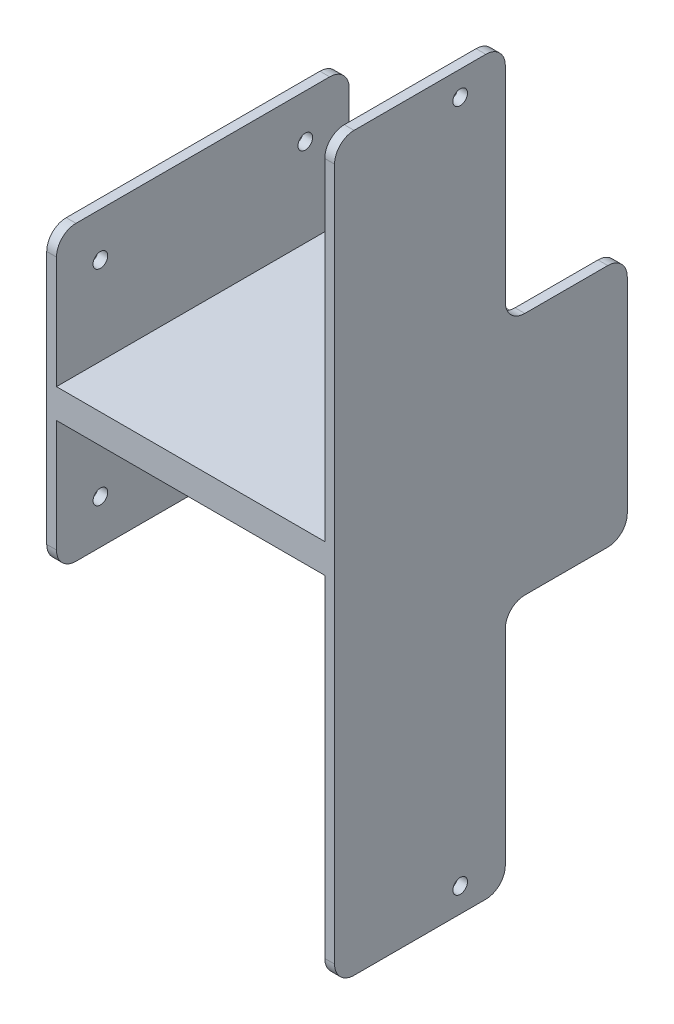
SolidWorks part; units mm, degrees
ref_plane "前视基准面" through (0, 0, 0) normal (0, 0, 1) x (1, 0, 0)
ref_plane "上视基准面" through (0, 0, 0) normal (0, 1, 0) x (1, 0, 0)
ref_plane "右视基准面" through (0, 0, 0) normal (1, 0, 0) x (0, 0, -1)
sketch "草图1" plane through (0, 0, 0) normal (0, 0, 1) x (1, 0, 0)
  line L0 (0, 0) -> (0, 50000) construction
  line L5 (-29.5, 30) -> (-27.5, 30)
  line L6 (-29.5, 30) -> (-29.5, -30)
  line L7 (-29.5, -30) -> (-27.5, -30)
  line L8 (-27.5, 30) -> (-27.5, 3)
  line L9 (27.5, -3) -> (27.5, -25)
  line L10 (-27.5, 3) -> (27.5, 3)
  line L12 (-27.5, -3) -> (27.5, -3)
  line L14 (27.5, 25) -> (29.5, 25)
  line L15 (27.5, 25) -> (27.5, 3)
  line L16 (27.5, -25) -> (29.5, -25)
  line L17 (29.5, 25) -> (29.5, -25)
  line L18 (-27.5, -3) -> (-27.5, -30)
  dimension "D1" = 55
  dimension "D2" = 2
  dimension "D3" = 2
  dimension "D4" = 6
  dimension "D5" = 3
  dimension "D6" = 50
  dimension "D7" = 25
  dimension "D8" = 30
  dimension "D9" = 60
  dimension "D10" = 27.5
extrude "凸台-拉伸2" add sketch "草图1" along normal blind 60
sketch "草图3" plane through (-29.5, 0, 0) normal (-1, 0, 0) x (0, 0, 1)
  line L1 (9, 21) -> (51, 21) construction
  line L2 (9, 21) -> (9, -21) construction
  line L3 (9, -21) -> (51, -21) construction
  line L4 (51, 21) -> (51, -21) construction
  circle A0 centre (51, 21) radius 1.5
  circle A1 centre (51, -21) radius 1.5
  circle A2 centre (9, 21) radius 1.5
  circle A3 centre (9, -21) radius 1.5
  dimension "D4" = 3
  dimension "D1" = 42
  dimension "D2" = 21
  dimension "D3" = 9
extrude "切除-拉伸1" cut sketch "草图3" against normal blind 40
sketch "草图7" plane through (27.5, 0, 0) normal (-1, 0, 0) x (0, 0, 1)
  line L0 (0, 0) -> (50000, 0) construction
  line L1 (25, 25) -> (60, 25)
  line L2 (25, 25) -> (25, 75)
  line L3 (25, 75) -> (60, 75)
  line L4 (60, 25) -> (60, 75)
  line L5 (60, -25) -> (60, -75)
  line L6 (25, -75) -> (60, -75)
  line L7 (25, -25) -> (25, -75)
  line L8 (25, -25) -> (60, -25)
  line L9 (0, 30) -> (0, -30) construction
  dimension "D1" = 50
  dimension "40" = 35
  dimension "D3" = 25
  dimension "D4" = 25
extrude "凸台-拉伸4" add sketch "草图7" against normal blind 2
sketch "草图8" plane through (27.5, 0, 0) normal (-1, 0, 0) x (0, 0, 1)
  line L0 (0, 0) -> (50000, 0) construction
  circle A0 centre (34.25, 70) radius 1.5
  circle A1 centre (9, 21) radius 1.5 construction
  circle A2 centre (34.25, -70) radius 1.5
  dimension "D1" = 49
  dimension "D3" = 3
  dimension "D2" = 25.25
extrude "切除-拉伸3" cut sketch "草图8" against normal blind 12
fillet "圆角1" radius 4 12 edges at (-28.5, 30, 60) (-28.5, -30, 60) (28.5, 75, 60) (28.5, 75, 25) (28.5, -75, 60) (28.5, -75, 25) (28.5, -25, 25) (28.5, 25, 0) (28.5, -25, 0) (-28.5, 30, 0) (-28.5, -30, 0) (28.5, 25, 25)
